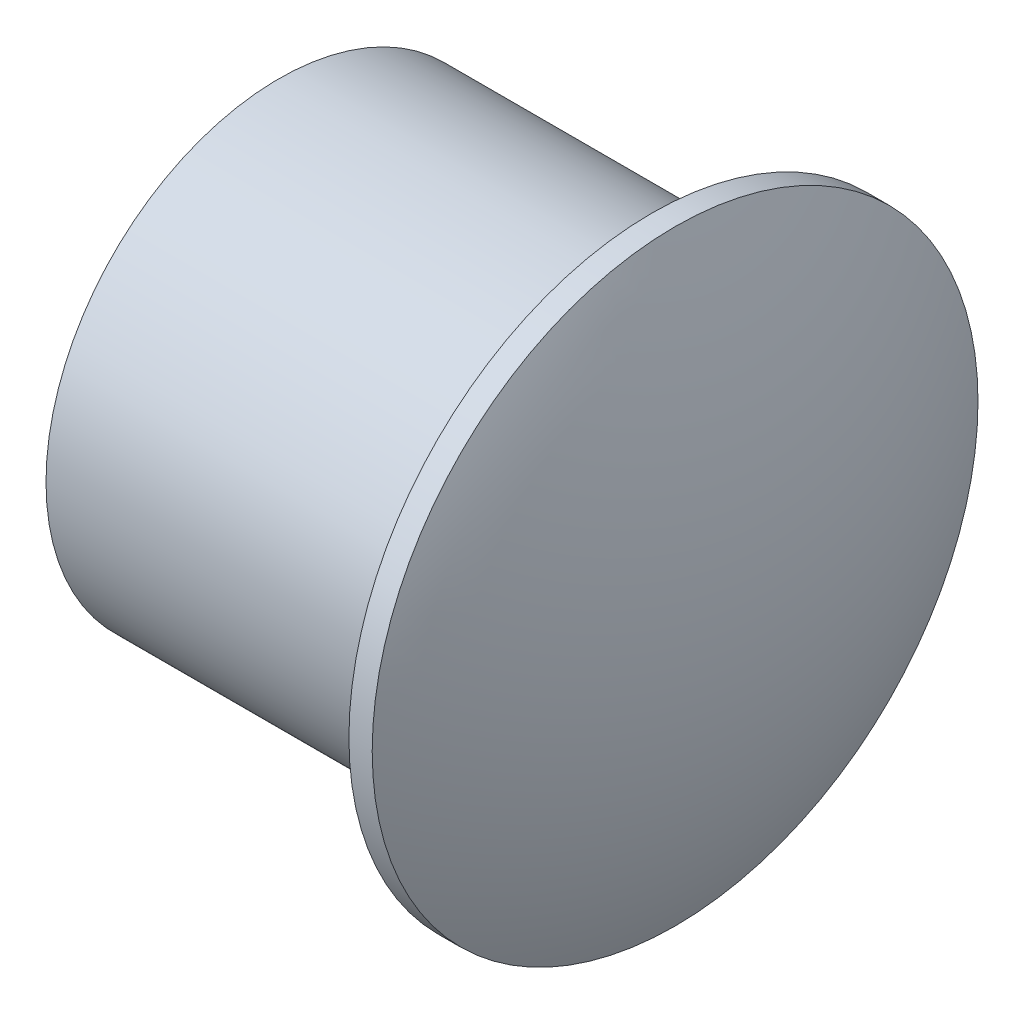
SolidWorks part; units mm, degrees
ref_plane "Front Plane" through (0, 0, 0) normal (0, 0, 1) x (1, 0, 0)
ref_plane "Top Plane" through (0, 0, 0) normal (0, 1, 0) x (1, 0, 0)
ref_plane "Right Plane" through (0, 0, 0) normal (1, 0, 0) x (0, 0, -1)
sketch "Sketch1" plane through (0, 0, 0) normal (0, 0, 1) x (1, 0, 0)
  line L0 (0, 0) -> (0, 10)
  line L1 (0, 10) -> (16, 10)
  line L2 (16, 10) -> (16, 13)
  line L3 (16, 13) -> (17, 13)
  line L4 (0, 0) -> (20, 0)
  arc A0 (20, 0) -> (17, 13) centre (-9.6667, 0) ccw
  point P8 (16.395, 13)
  dimension "D1" = 20
  dimension "D2" = 10
  dimension "D3" = 16
  dimension "D4" = 3
  dimension "D5" = 1
revolve "Revolve1" add sketch "Sketch1" angle 360 about L4
